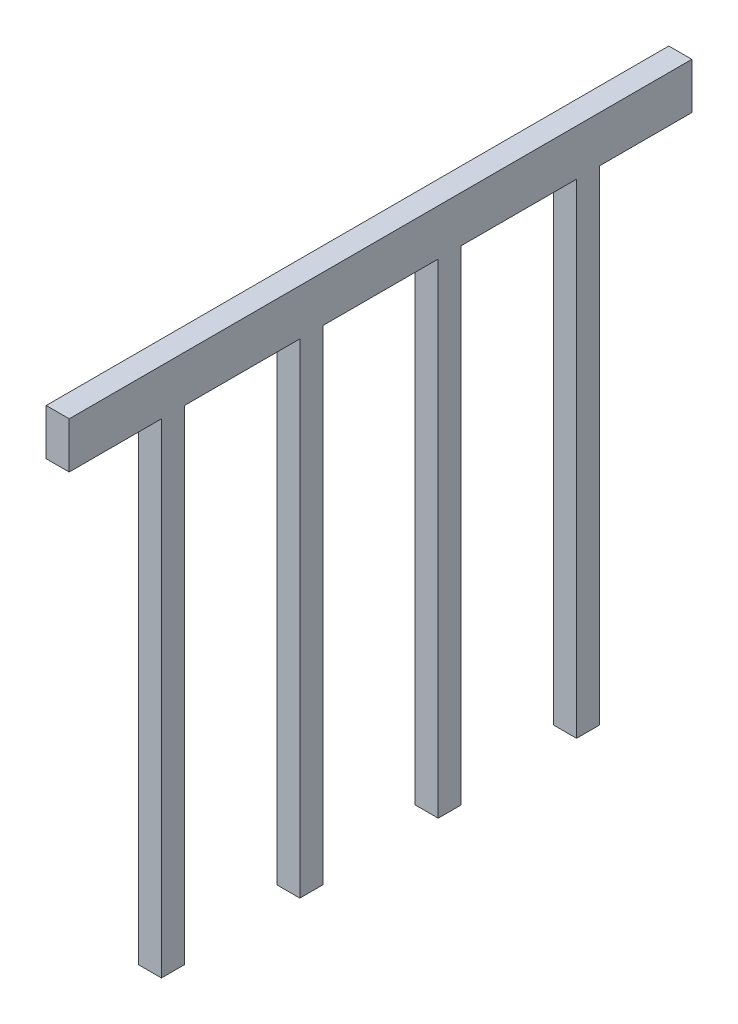
SolidWorks part; units mm, degrees
ref_plane "Front Plane" through (0, 0, 0) normal (0, 0, 1) x (1, 0, 0)
ref_plane "Top Plane" through (0, 0, 0) normal (0, 1, 0) x (1, 0, 0)
ref_plane "Right Plane" through (0, 0, 0) normal (1, 0, 0) x (0, 0, -1)
sketch "Sketch1" plane through (0, 0, 0) normal (1, 0, 0) x (0, 0, -1)
  line B0 (-215.9, 463.677) -> (-215.9, 533.4) construction
  line B1 (-215.9, 533.4) -> (-285.623, 533.4) construction
  line B2 (-285.623, 516.9719) -> (-232.3281, 463.677) construction
  line B3 (285.623, 533.4) -> (215.9, 533.4) construction
  line B4 (215.9, 533.4) -> (215.9, 463.677) construction
  line B5 (215.9, 463.677) -> (232.3281, 463.677) construction
  line B6 (232.3281, 463.677) -> (285.623, 516.9719) construction
  line B7 (285.623, 516.9719) -> (285.623, 533.4) construction
  line B8 (-215.9, 0) -> (-165.1, 0) construction
  line B9 (-215.9, 0) -> (-215.9, 584.2) construction
  line B10 (-165.1, 0) -> (-165.1, 533.4) construction
  line B11 (215.9, -0.381) -> (165.1, -0.381) construction
  line B12 (215.9, -0.381) -> (215.9, 584.2) construction
  line B13 (165.1, -0.381) -> (165.1, 533.4) construction
  line B14 (368.3, 584.2) -> (-368.3, 584.2) construction
  line B15 (368.3, 584.2) -> (368.3, 533.4) construction
  line B16 (368.3, 533.4) -> (-368.3, 533.4) construction
  line B17 (-368.3, 584.2) -> (-368.3, 533.4) construction
  line B18 (0, 533.4) -> (0, -227.9457) construction
  line B19 (-285.623, 533.4) -> (-285.623, 516.9719) construction
  line B20 (-232.3281, 463.677) -> (-215.9, 463.677) construction
sketch_block_instance "Block3-1"
sketch_block "Block3" parameters "D1"=50.8, "D2"=50.8, "D3"=584.2, "D4"=533.4, "D5"=50.8
sketch_block_instance "Block1-2"
sketch_block "Block1" parameters "D1"=69.723, "D2"=69.723, "D3"=75.3703, "D4"=16.4281, "D5"=16.4281, "D6"=90, "D7"=90, "D8"=90, "D9"=135, "D10"=135
sketch_block_instance "Block1-1"
sketch "Sketch2" plane through (0, 0, 0) normal (1, 0, 0) x (0, 0, -1)
  line L0 (-368.3, 584.2) -> (368.3, 584.2)
  line L1 (368.3, 584.2) -> (368.3, 533.4)
  line L2 (368.3, 533.4) -> (215.9, 533.4)
  line L3 (215.9, 533.4) -> (215.9, -0.381)
  line L4 (215.9, -0.381) -> (165.1, -0.381)
  line L5 (165.1, -0.381) -> (165.1, 533.4)
  line L6 (165.1, 533.4) -> (-165.1, 533.4)
  line L7 (-165.1, 533.4) -> (-165.1, 0)
  line L8 (-165.1, 0) -> (-215.9, 0)
  line L9 (-215.9, 0) -> (-215.9, 533.4)
  line L10 (-215.9, 533.4) -> (-368.3, 533.4)
  line L11 (-368.3, 533.4) -> (-368.3, 584.2)
sketch "Sketch3" plane through (0, 0, 0) normal (1, 0, 0) x (0, 0, -1)
  line L0 (-63.5, 449.6559) -> (63.5, 449.6559) construction
  line L1 (-342.9, 584.2) -> (342.9, 584.2)
  line L2 (-342.9, 584.2) -> (-342.9, 533.4)
  line L3 (-342.9, 533.4) -> (-241.3, 533.4)
  line L4 (342.9, 584.2) -> (342.9, 533.4)
  line L6 (-241.3, 533.4) -> (-241.3, 0)
  line L7 (-241.3, 0) -> (-215.9, 0)
  line L8 (-215.9, 533.4) -> (-215.9, 0)
  line L10 (-88.9, 533.4) -> (-88.9, 0)
  line L11 (-88.9, 0) -> (-63.5, 0)
  line L12 (-63.5, 533.4) -> (-63.5, 0)
  line L14 (63.5, 533.4) -> (63.5, 0)
  line L15 (63.5, 0) -> (88.9, 0)
  line L16 (88.9, 533.4) -> (88.9, 0)
  line L18 (215.9, 533.4) -> (215.9, 0)
  line L19 (215.9, 0) -> (241.3, 0)
  line L20 (241.3, 533.4) -> (241.3, 0)
  line L21 (0, 638.0339) -> (0, -91.9966) construction
  line L22 (0, 533.4) -> (0, -227.9457) construction
  line L23 (-215.9, 533.4) -> (-88.9, 533.4)
  line L24 (-63.5, 533.4) -> (63.5, 533.4)
  line L25 (88.9, 533.4) -> (215.9, 533.4)
  line L26 (241.3, 533.4) -> (342.9, 533.4)
  point P24 (0, 584.2)
  point P27 (0, 449.6559)
  dimension "D1" = 685.8
  dimension "D2" = 25.4
  dimension "D3" = 533.4
  dimension "D5" = 50.8
  dimension "D6" = 127
  dimension "D4" = 4
extrude "Boss-Extrude1" add sketch "Sketch3" along normal blind 25.4
